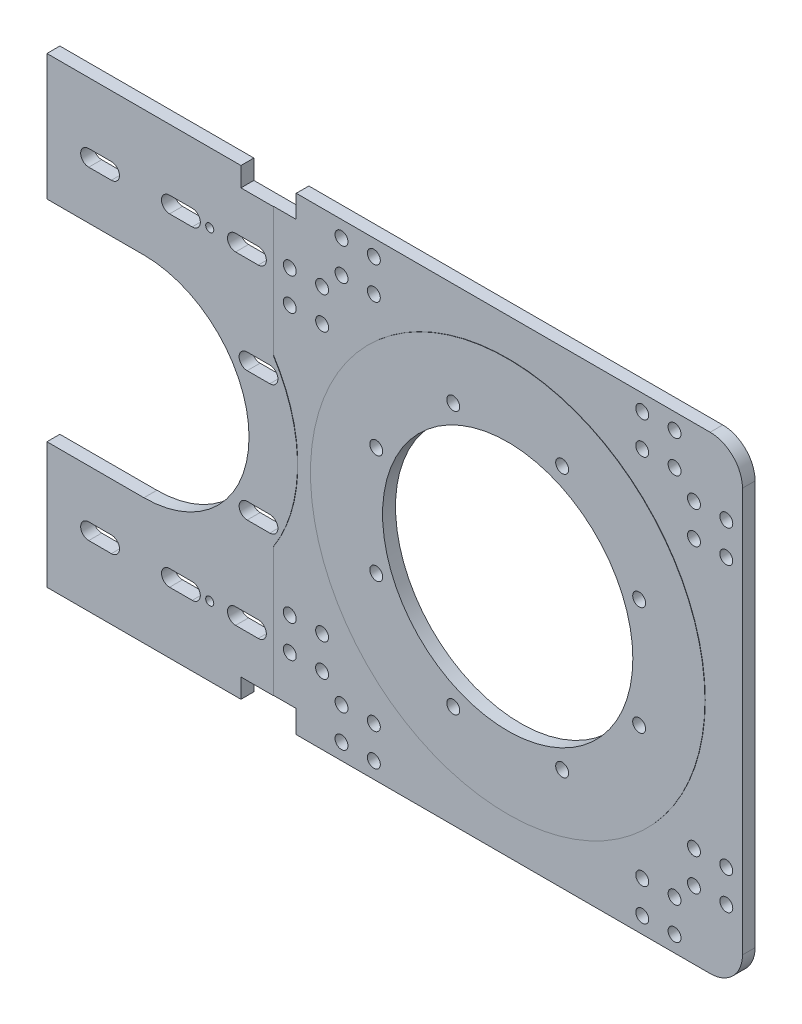
SolidWorks part; units mm, degrees
material "6061 合金"
ref_plane "前视基准面" through (0, 0, 0) normal (0, 0, 1) x (1, 0, 0)
ref_plane "上视基准面" through (0, 0, 0) normal (0, 1, 0) x (1, 0, 0)
ref_plane "右视基准面" through (0, 0, 0) normal (1, 0, 0) x (0, 0, -1)
other "Configuration Table"
sketch "草图1" plane through (0, 0, 0) normal (0, 0, 1) x (1, 0, 0)
  line L0 (0, 0) -> (16.8381, 40.6507)
  line L1 (-72.5, 72.5) -> (72.5, 72.5)
  line L2 (-72.5, 72.5) -> (-72.5, -72.5)
  line L3 (-72.5, -72.5) -> (72.5, -72.5)
  line L4 (72.5, 72.5) -> (72.5, -72.5)
  line L5 (-72.5, 72.5) -> (72.5, -72.5) construction
  line L6 (-72.5, -72.5) -> (72.5, 72.5) construction
  circle A0 centre (0, 0) radius 44 construction
  circle A1 centre (0, 0) radius 38.7
  circle A2 centre (16.8381, 40.6507) radius 2
  circle A3 centre (40.6507, 16.8381) radius 2
  circle A4 centre (40.6507, -16.8381) radius 2
  circle A5 centre (16.8381, -40.6507) radius 2
  circle A6 centre (-16.8381, -40.6507) radius 2
  circle A7 centre (-40.6507, -16.8381) radius 2
  circle A8 centre (-40.6507, 16.8381) radius 2
  circle A9 centre (-16.8381, 40.6507) radius 2
  point P0 (0, 0)
  point P28 (0, 0)
  dimension "D3" = 88
  dimension "D4" = 77.4
  dimension "D7" = 4
  dimension "D1" = 145
  dimension "D2" = 145
  dimension "D5" = 22.5
  dimension "D6" = 8
extrude "凸台-拉伸1" add sketch "草图1" along normal blind 4
sketch "草图2" plane through (0, 0, 4) normal (0, 0, 1) x (1, 0, 0)
  circle A0 centre (0, 0) radius 61
  dimension "D1" = 122
extrude "切除-拉伸1" cut sketch "草图2" against normal blind 0.1 flip side to cut
sketch "草图3" plane through (0, 0, 0) normal (0, 0, -1) x (-1, 0, 0)
  line L1 (97.5, -72.5) -> (72.5, -72.5)
  line L2 (97.5, -72.5) -> (97.5, 72.5)
  line L3 (97.5, 72.5) -> (72.5, 72.5)
  line L4 (72.5, -72.5) -> (72.5, 72.5)
  line L5 (97.5, -72.5) -> (72.5, 72.5) construction
  line L6 (97.5, 72.5) -> (72.5, -72.5) construction
  line L7 (79.5, 65.5) -> (72.5, 65.5)
  line L8 (79.5, 65.5) -> (79.5, 72.5)
  line L9 (79.5, 72.5) -> (72.5, 72.5)
  line L10 (72.5, 65.5) -> (72.5, 72.5)
  line L11 (79.5, 65.5) -> (72.5, 72.5) construction
  line L12 (79.5, 72.5) -> (72.5, 65.5) construction
  line L13 (79.5, -65.5) -> (72.5, -65.5)
  line L14 (79.5, -65.5) -> (79.5, -72.5)
  line L15 (79.5, -72.5) -> (72.5, -72.5)
  line L16 (72.5, -65.5) -> (72.5, -72.5)
  line L17 (79.5, -65.5) -> (72.5, -72.5) construction
  line L18 (79.5, -72.5) -> (72.5, -65.5) construction
  circle A0 centre (112.5, 0) radius 47.5
  circle A1 centre (92.1546, -50) radius 1.25 construction
  circle A2 centre (84.1546, -50) radius 1.25 construction
  circle A3 centre (84.1546, 50) radius 1.25 construction
  circle A4 centre (92.1546, 50) radius 1.25 construction
  circle A5 centre (92.1546, -50) radius 1.25
  circle A6 centre (84.1546, -50) radius 1.25
  circle A7 centre (84.1546, 50) radius 1.25
  circle A8 centre (92.1546, 50) radius 1.25
  point P0 (85, 0)
  point P8 (76, 69)
  point P10 (76, -69)
  dimension "D1" = 95
  dimension "D2" = 25
  dimension "D3" = 112.5
  dimension "D4" = 7
  dimension "D5" = 7
  dimension "D6" = 7
  dimension "D7" = 7
extrude "凸台-拉伸2" add sketch "草图3" against normal blind 4 contours A0 L2 L3 L8 L7 L4 | A0 L4 L13 L14 L1 L2
sketch "草图5" plane through (0, 0, 0) normal (0, 0, -1) x (-1, 0, 0)
  line L0 (-72.5, 72.5) -> (-72.5, -72.5) construction
  line L1 (72.5, 72.5) -> (-72.5, 72.5) construction
  line L2 (0, 0) -> (-72.5, 0) construction
  line L3 (0, 0) -> (0, 72.5) construction
  circle A0 centre (-67.5, 41.5) radius 2
  circle A1 centre (-41.5, 67.5) radius 2
  circle A2 centre (-51.5, 67.5) radius 2
  circle A3 centre (-51.5, 57.5) radius 2
  circle A4 centre (-41.5, 57.5) radius 2
  circle A5 centre (-57.5, 41.5) radius 2
  circle A6 centre (-57.5, 51.5) radius 2
  circle A7 centre (-67.5, 51.5) radius 2
  circle A8 centre (67.5, 51.5) radius 2
  circle A9 centre (57.5, 51.5) radius 2
  circle A10 centre (57.5, 41.5) radius 2
  circle A11 centre (41.5, 57.5) radius 2
  circle A12 centre (51.5, 57.5) radius 2
  circle A13 centre (51.5, 67.5) radius 2
  circle A14 centre (41.5, 67.5) radius 2
  circle A15 centre (67.5, 41.5) radius 2
  circle A16 centre (67.5, -41.5) radius 2
  circle A17 centre (41.5, -67.5) radius 2
  circle A18 centre (51.5, -67.5) radius 2
  circle A19 centre (51.5, -57.5) radius 2
  circle A20 centre (41.5, -57.5) radius 2
  circle A21 centre (57.5, -41.5) radius 2
  circle A22 centre (57.5, -51.5) radius 2
  circle A23 centre (67.5, -51.5) radius 2
  circle A24 centre (-67.5, -51.5) radius 2
  circle A25 centre (-57.5, -51.5) radius 2
  circle A26 centre (-57.5, -41.5) radius 2
  circle A27 centre (-41.5, -57.5) radius 2
  circle A28 centre (-51.5, -57.5) radius 2
  circle A29 centre (-51.5, -67.5) radius 2
  circle A30 centre (-41.5, -67.5) radius 2
  circle A31 centre (-67.5, -41.5) radius 2
  dimension "D5" = 4
  dimension "D7" = 31
  dimension "D8" = 31
  dimension "D9" = 5
  dimension "D6" = 5
  dimension "D1" = 2
  dimension "D2" = 2
  dimension "D3" = 2
  dimension "D4" = 2
extrude "切除-拉伸2" cut sketch "草图5" against normal blind 4
sketch "草图6" plane through (0, 0, 0) normal (0, 0, -1) x (-1, 0, 0)
  line L0 (-57.5, -41.5) -> (-57.5, -51.5) construction
  line L1 (-51.5, -57.5) -> (-41.5, -57.5) construction
  line L2 (72.5, 65.5) -> (-72.5, 65.5)
  line L3 (31.5, 65.5) -> (-31.5, 65.5)
  line L4 (-41.5, -57.5) -> (-41.5, -67.5) construction
  line L5 (72.5, -65.5) -> (-72.5, -65.5)
  line L6 (31.5, -65.5) -> (-31.5, -65.5)
  line L7 (-31.5, -57.5) -> (-31.5, -65.5)
  line L8 (-31.5, -57.5) -> (-31.5, -42)
  line L9 (-31.5, -57.5) -> (-31.5, -67.5) construction
  line L10 (0, 0) -> (0, -72.5) construction
  line L11 (72.5, -72.5) -> (-72.5, -72.5) construction
  line L12 (0, 0) -> (-72.5, 0) construction
  line L13 (-72.5, 72.5) -> (-72.5, -72.5) construction
  line L14 (31.5, -57.5) -> (31.5, -65.5)
  line L15 (31.5, -57.5) -> (31.5, -42)
  line L16 (31.5, 57.5) -> (31.5, 42)
  line L17 (31.5, 57.5) -> (31.5, 65.5)
  line L18 (31.5, 65.5) -> (-31.5, 65.5)
  line L19 (-31.5, 57.5) -> (-31.5, 65.5)
  line L20 (-31.5, 57.5) -> (-31.5, 42)
  line L21 (-52.5, -37.5) -> (-52.5, -52.5)
  line L22 (-67.5, -41.5) -> (-57.5, -41.5) construction
  line L23 (-65.5, 72.5) -> (-65.5, -72.5)
  line L24 (-65.5, 31.5) -> (-65.5, -31.5)
  line L25 (-65.5, 31.5) -> (-42, 31.5)
  line L26 (-65.5, -31.5) -> (-42, -31.5)
  line L27 (65.5, 31.5) -> (42, 31.5)
  line L28 (65.5, -31.5) -> (42, -31.5)
  line L29 (-52.5, -52.5) -> (-37.5, -52.5)
  line L30 (-52.5, -41.5) -> (-52.5, -51.5) construction
  line L31 (-52.5, -37.5) -> (-40.2337, -37.5)
  line L32 (65.5, 31.5) -> (65.5, -31.5)
  line L33 (-37.5, -52.5) -> (-37.5, -40.2337)
  line L34 (52.5, -37.5) -> (40.2337, -37.5)
  line L35 (52.5, -37.5) -> (52.5, -52.5)
  line L36 (52.5, -52.5) -> (37.5, -52.5)
  line L37 (37.5, -52.5) -> (37.5, -40.2337)
  line L38 (52.5, 37.5) -> (40.2337, 37.5)
  line L39 (37.5, 52.5) -> (37.5, 40.2337)
  line L40 (52.5, 52.5) -> (37.5, 52.5)
  line L41 (52.5, 37.5) -> (52.5, 52.5)
  line L42 (-37.5, 52.5) -> (-37.5, 40.2337)
  line L43 (-52.5, 37.5) -> (-40.2337, 37.5)
  line L44 (-52.5, 52.5) -> (-37.5, 52.5)
  line L45 (-52.5, 37.5) -> (-52.5, 52.5)
  line L46 (-72.5, 72.5) -> (-52.5, 52.5) construction
  line L47 (-56.5, -68.5) -> (-56.5, -56.5)
  line L48 (-68.5, 68.5) -> (-56.5, 68.5)
  line L49 (-68.5, 68.5) -> (-68.5, 56.5)
  line L50 (-68.5, 56.5) -> (-56.5, 56.5)
  line L51 (-56.5, 68.5) -> (-56.5, 56.5)
  line L52 (-68.5, 68.5) -> (-56.5, 56.5) construction
  line L53 (-68.5, 56.5) -> (-56.5, 68.5) construction
  line L54 (-68.5, -68.5) -> (-56.5, -68.5)
  line L55 (-68.5, -68.5) -> (-68.5, -56.5)
  line L56 (-68.5, -56.5) -> (-56.5, -56.5)
  circle A0 centre (0, 0) radius 52.5
  circle A1 centre (57.5, -41.5) radius 2 construction
  arc A2 (-40.2337, -37.5) -> (-37.5, -40.2337) centre (0, 0) ccw
  circle A3 centre (41.5, 57.5) radius 2 construction
  arc A4 (-37.5, 40.2337) -> (-40.2337, 37.5) centre (0, 0) ccw
  arc A5 (40.2337, 37.5) -> (37.5, 40.2337) centre (0, 0) ccw
  arc A6 (37.5, -40.2337) -> (40.2337, -37.5) centre (0, 0) ccw
  arc A7 (37.5, 40.2337) -> (40.2337, 37.5) centre (0, 0) cw
  arc A8 (-40.2337, 37.5) -> (-37.5, 40.2337) centre (0, 0) cw
  circle A11 centre (-67.5, 51.5) radius 2 construction
  dimension "D1" = 105
  dimension "D7" = 10
  dimension "D9" = 110
  dimension "D13" = 5
  dimension "D6" = 10
  dimension "D10" = 15
  dimension "D11" = 6
  dimension "D12" = 4
  dimension "D2" = 7
  dimension "D3" = 7
  dimension "D4" = 10
  dimension "D5" = 7
  dimension "D8" = 5
extrude "切除-拉伸3" [suppressed] cut sketch "草图6" against normal blind 3 contours A0 L25 L24 L26 | A2 L31 L21 L29 L33 | A0 L8 L7 L6 L14 L15 | A6 L37 L36 L35 L34 | A0 L28 L32 L27 | A5 L38 L41 L40 L39 | A0 L16 L17 L3 L19 L20 | A4 L42 L44 L45 L43 | L51 L48 L49 L50 | L56 L55 L54 L47
fillet "圆角1" [suppressed] radius 3
sketch "草图7" plane through (0, 0, 0) normal (0, 0, -1) x (-1, 0, 0)
  line L0 (97.5, 72.5) -> (79.5, 72.5) construction
  line L1 (97.5, 72.5) -> (65.5, 72.5)
  line L2 (97.5, 72.5) -> (97.5, 65.4886)
  line L3 (65.5, 72.5) -> (65.5, 65.4886)
  line L4 (97.5, 65.4886) -> (65.5, 65.4886)
  line L6 (97.5, -72.5) -> (65.5, -72.5)
  line L7 (97.5, -72.5) -> (97.5, -65.5)
  line L8 (97.5, -65.5) -> (65.5, -65.5)
  line L9 (65.5, -72.5) -> (65.5, -65.5)
  circle A0 centre (112.5, 0) radius 47.5
  dimension "D1" = 32
  dimension "D2" = 32
extrude "切除-拉伸4" cut sketch "草图7" against normal blind 4
sketch "草图8" plane through (0, 0, 0) normal (0, 0, -1) x (-1, 0, 0)
  line L0 (65.5, 65.4886) -> (97.5, 65.4886) construction
  line L1 (82.5, 65.4886) -> (97.5, 65.4886)
  line L2 (82.5, 65.4886) -> (82.5, 71.4886)
  line L3 (82.5, 71.4886) -> (97.5, 71.4886)
  line L4 (97.5, 65.4886) -> (97.5, 71.4886)
  line L5 (97.5, 45.0694) -> (97.5, 65.4886) construction
  dimension "D1" = 15
  dimension "D2" = 6
extrude "凸台-拉伸3" add sketch "草图8" against normal blind 4
sketch "草图10" plane through (0, 0, 4) normal (0, 0, 1) x (1, 0, 0)
  line L0 (-82.5, 71.4886) -> (-82.5, 65.4886) construction
  line L1 (-97.5, 71.4886) -> (-92.4004, 71.4886)
  line L2 (-97.5, 71.4886) -> (-97.5, 54.0886)
  line L3 (-97.5, 54.0886) -> (-92.5, 54.0886)
  line L4 (-92.5, 64.0886) -> (-92.5, 54.0886)
  line L5 (-92.4004, 71.4886) -> (-82.5, 71.4886)
  line L7 (-92.5, 64.0886) -> (-82.5, 64.0886)
  line L8 (-82.5, 71.4886) -> (-82.5, 64.0886)
  circle A0 centre (-93.5, 67.4886) radius 1.25
  circle A1 centre (-86.5, 67.4886) radius 1.25
  dimension "D4" = 2.5
  dimension "D5" = 2.5
  dimension "D6" = 4
  dimension "D7" = 4
  dimension "D8" = 4
  dimension "D9" = 4
  dimension "D1" = 17.4
  dimension "D2" = 10
  dimension "D3" = 5
  dimension "D10" = 54.0886
extrude "凸台-拉伸4" [suppressed] add sketch "草图10" along normal blind 11
sketch "草图11" [suppressed] plane through (-92.5, 0, 0) normal (1, 0, 0) x (0, 0, -1)
  line L0 (-15, 54.0886) -> (-15, 64.0886) construction
  circle A0 centre (-10, 59.5) radius 2.5
  dimension "D1" = 5
  dimension "D3" = 59.5
  dimension "D2" = 5
extrude "切除-拉伸5" [suppressed] cut sketch "草图11" against normal blind 10
fillet "圆角2" [suppressed] radius 2
fillet "圆角3" [suppressed] radius 1
mirror "镜向1" about plane through (0, 0, 0) normal (0, 1, 0) of "凸台-拉伸3", "凸台-拉伸4", "切除-拉伸5", "圆角2", "圆角3"
fillet "圆角4" radius 10 2 edges at (72.5, -72.5, 1.95) (72.5, 72.5, 1.95)
sketch "草图12" plane through (0, 0, 0) normal (0, 0, -1) x (-1, 0, 0)
  line L0 (84.1546, 50) -> (77.1546, 50) construction
  line L1 (84.1546, 47.5) -> (77.1546, 47.5)
  line L2 (84.1546, 52.5) -> (77.1546, 52.5)
  line L3 (84.1546, -50) -> (77.1546, -50) construction
  line L4 (84.1546, -52.5) -> (77.1546, -52.5)
  line L5 (84.1546, -47.5) -> (77.1546, -47.5)
  arc A0 (84.1546, 47.5) -> (84.1546, 52.5) centre (84.1546, 50) ccw
  arc A1 (77.1546, 52.5) -> (77.1546, 47.5) centre (77.1546, 50) ccw
  arc A2 (84.1546, -52.5) -> (84.1546, -47.5) centre (84.1546, -50) ccw
  arc A3 (77.1546, -47.5) -> (77.1546, -52.5) centre (77.1546, -50) ccw
  point P3 (80.6546, 50)
  point P11 (80.6546, -50)
  dimension "D2" = 2.5
  dimension "D4" = 2.5
  dimension "D1" = 7
  dimension "D3" = 7
extrude "切除-拉伸6" cut sketch "草图12" against normal blind 4
sketch "草图13" plane through (0, 0, 0) normal (0, 0, -1) x (-1, 0, 0)
  line L0 (97.5, -71.4886) -> (142.5, -71.4886)
  line L1 (142.5, -71.4886) -> (142.5, -32.5)
  line L2 (97.5, -71.4886) -> (97.5, -45.0694) construction
  line L3 (97.5, 45.0694) -> (97.5, 71.4886) construction
  line L4 (97.5, -71.4886) -> (97.5, -45.0694)
  line L5 (97.5, 45.0694) -> (97.5, 71.4886)
  line L6 (0, 0) -> (18.6604, 0) construction
  line L7 (142.5, 71.4886) -> (142.5, 32.5)
  line L8 (97.5, 71.4886) -> (142.5, 71.4886)
  line L9 (112.5, 32.5) -> (142.5, 32.5)
  line L10 (112.5, -32.5) -> (142.5, -32.5)
  arc A0 (112.5, 32.5) -> (112.5, -32.5) centre (112.5, 0) ccw
  arc A1 (97.5, 45.0694) -> (97.5, -45.0694) centre (112.5, 0) ccw construction
  arc A2 (97.5, 45.0694) -> (97.5, -45.0694) centre (112.5, 0) ccw
  dimension "D1" = 45
  dimension "D2" = 32.5
extrude "凸台-拉伸5" add sketch "草图13" against normal blind 4 contours L5 A2 L4 L0 L1 A0 L7 L8
sketch "草图14" plane through (0, 0, 0) normal (0, 0, -1) x (-1, 0, 0)
  line L0 (97.567, 50) -> (104.567, 50) construction
  line L1 (97.567, 52.5) -> (104.567, 52.5)
  line L2 (97.567, 47.5) -> (104.567, 47.5)
  line L3 (122.567, 50) -> (129.567, 50) construction
  line L4 (122.567, 52.5) -> (129.567, 52.5)
  line L5 (122.567, 47.5) -> (129.567, 47.5)
  line L6 (0, 0) -> (19.1425, 0) construction
  line L7 (122.567, -50) -> (129.567, -50) construction
  line L8 (122.567, -52.5) -> (129.567, -52.5)
  line L9 (122.567, -47.5) -> (129.567, -47.5)
  line L10 (97.567, -50) -> (104.567, -50) construction
  line L11 (97.567, -52.5) -> (104.567, -52.5)
  line L12 (97.567, -47.5) -> (104.567, -47.5)
  arc A0 (97.567, 52.5) -> (97.567, 47.5) centre (97.567, 50) ccw
  arc A1 (104.567, 47.5) -> (104.567, 52.5) centre (104.567, 50) ccw
  arc A2 (122.567, 52.5) -> (122.567, 47.5) centre (122.567, 50) ccw
  arc A3 (129.567, 47.5) -> (129.567, 52.5) centre (129.567, 50) ccw
  arc A4 (122.567, -52.5) -> (122.567, -47.5) centre (122.567, -50) cw
  arc A5 (129.567, -47.5) -> (129.567, -52.5) centre (129.567, -50) cw
  arc A6 (97.567, -52.5) -> (97.567, -47.5) centre (97.567, -50) cw
  arc A7 (104.567, -47.5) -> (104.567, -52.5) centre (104.567, -50) cw
  point P3 (101.067, 50)
  point P8 (126.067, 50)
  point P20 (126.067, -50)
  point P27 (101.067, -50)
  dimension "D1" = 2.5
  dimension "D4" = 2.5
  dimension "D2" = 18
  dimension "D3" = 7
  dimension "D5" = 7
extrude "切除-拉伸7" cut sketch "草图14" against normal blind 4
sketch "草图15" [suppressed] plane through (0, 0, 4) normal (0, 0, 1) x (1, 0, 0)
  line L0 (-91.5, 64.0886) -> (-83.5, 64.0886) construction
  line L1 (-107.5, 64.0886) -> (-97.5, 64.0886)
  line L2 (-107.5, 64.0886) -> (-107.5, 71.4886)
  line L3 (-107.5, 71.4886) -> (-97.5, 71.4886)
  line L4 (-97.5, 64.0886) -> (-97.5, 71.4886)
  line L5 (-107.5, 64.0886) -> (-97.5, 71.4886) construction
  line L6 (-107.5, 71.4886) -> (-97.5, 64.0886) construction
  line L7 (-97.5, -71.4886) -> (-142.5, -71.4886) construction
  line L8 (-107.5, -64.0886) -> (-97.5, -64.0886)
  line L9 (-107.5, -64.0886) -> (-107.5, -71.4886)
  line L10 (-107.5, -71.4886) -> (-97.5, -71.4886)
  line L11 (-97.5, -64.0886) -> (-97.5, -71.4886)
  line L12 (-107.5, -64.0886) -> (-97.5, -71.4886) construction
  line L13 (-107.5, -71.4886) -> (-97.5, -64.0886) construction
  line L14 (-97.5, -71.4886) -> (-97.5, -55.0886) construction
  line L15 (-91.5, -64.0886) -> (-83.5, -64.0886) construction
  circle A0 centre (-100.5, -67.4886) radius 1.25
  circle A1 centre (-100.5, 67.4886) radius 1.25
  circle A2 centre (-93.5, 67.4886) radius 1.25 construction
  circle A3 centre (-93.5, -67.4886) radius 1.25 construction
  point P0 (-102.5, 67.7886)
  point P8 (-102.5, -67.7886)
  dimension "D3" = 4
  dimension "D4" = 2.5
  dimension "D5" = 7
  dimension "D6" = 4
  dimension "D7" = 2.5
  dimension "D8" = 7
  dimension "D1" = 10
  dimension "D2" = 10
extrude "凸台-拉伸6" [suppressed] add sketch "草图15" along normal blind 11
fillet "圆角5" [suppressed] radius 3
sketch "草图16" plane through (0, 0, 0) normal (0, 0, -1) x (-1, 0, 0)
  line L0 (73.567, 20) -> (80.567, 20) construction
  line L1 (73.567, 22.5) -> (80.567, 22.5)
  line L2 (73.567, 17.5) -> (80.567, 17.5)
  line L3 (112.5, 0) -> (102.0555, 0) construction
  line L4 (73.567, -20) -> (80.567, -20) construction
  line L5 (73.567, -22.5) -> (80.567, -22.5)
  line L6 (73.567, -17.5) -> (80.567, -17.5)
  circle A0 centre (73.567, 20) radius 2.5 construction
  arc A2 (97.567, 52.5) -> (97.567, 47.5) centre (97.567, 50) ccw construction
  arc A3 (73.567, 22.5) -> (73.567, 17.5) centre (73.567, 20) ccw
  arc A4 (80.567, 17.5) -> (80.567, 22.5) centre (80.567, 20) ccw
  circle A5 centre (73.567, -20) radius 2.5 construction
  arc A6 (73.567, -22.5) -> (73.567, -17.5) centre (73.567, -20) cw
  arc A7 (80.567, -17.5) -> (80.567, -22.5) centre (80.567, -20) cw
  point P5 (77.067, 20)
  point P18 (77.067, -20)
  dimension "D1" = 24
  dimension "D2" = 40
  dimension "D3" = 2.5
  dimension "D4" = 7
extrude "切除-拉伸8" cut sketch "草图16" against normal blind 4
sketch "草图17" [suppressed] plane through (0, 0, 0) normal (0, 0, -1) x (-1, 0, 0)
  line L0 (82.5, -71.4886) -> (142.5, -51.9943)
  line L1 (142.5, -68.4886) -> (142.5, -35.5) construction
  line L2 (142.5, -51.9943) -> (142.5, -71.4886)
  line L3 (142.5, -71.4886) -> (82.5, -71.4886)
  line L4 (82.5, 71.4886) -> (142.5, 51.9943)
  line L5 (142.5, 68.4886) -> (142.5, 35.5) construction
  line L6 (142.5, 51.9943) -> (142.5, 71.4886)
  line L7 (142.5, 71.4886) -> (82.5, 71.4886)
extrude "切除-拉伸9" [suppressed] cut sketch "草图17" against normal blind 4
